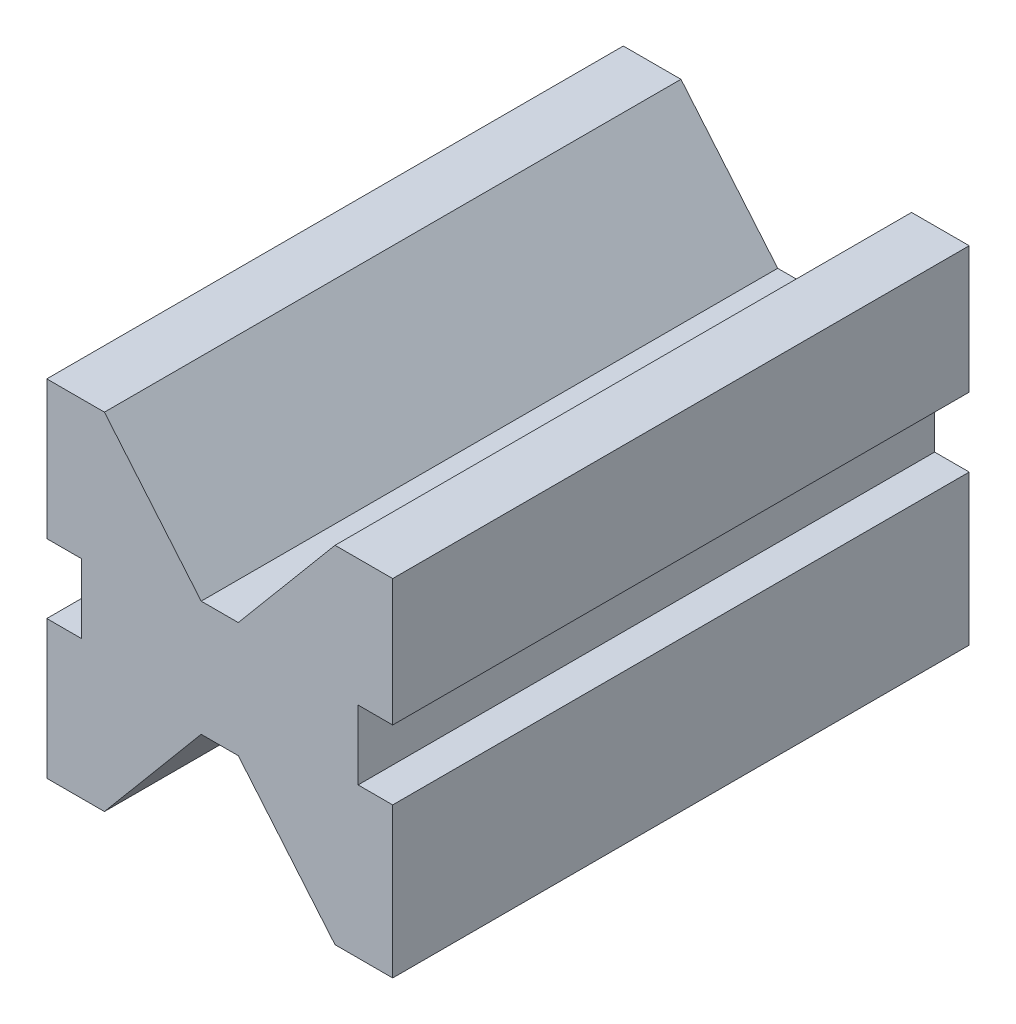
SolidWorks part; units mm, degrees
ref_plane "Ön Düzlem" through (0, 0, 0) normal (0, 0, 1) x (1, 0, 0)
ref_plane "Üst Düzlem" through (0, 0, 0) normal (0, 1, 0) x (1, 0, 0)
ref_plane "Sağ Düzlem" through (0, 0, 0) normal (1, 0, 0) x (0, 0, -1)
sketch "Çizim1" plane through (0, 0, 0) normal (0, 0, 1) x (1, 0, 0)
  line L0 (-50, 60) -> (-33.218, 40)
  line L1 (0, 0) -> (-10, 0)
  line L2 (0, 0) -> (0, 26.0026)
  line L3 (0, 60) -> (-10, 60)
  line L4 (-60, 0) -> (-60, 24)
  line L5 (-60, 36) -> (-54, 36)
  line L7 (-60, 24) -> (-54, 24)
  line L8 (-54, 36) -> (-54, 24)
  line L9 (0, 26.0026) -> (-6, 26.0026)
  line L11 (0, 38.0026) -> (-6, 38.0026)
  line L12 (-6, 26.0026) -> (-6, 38.0026)
  line L13 (-33.218, 40) -> (-26.782, 40)
  line L14 (-26.782, 40) -> (-10, 60)
  line L15 (-50, 0) -> (-33.218, 20)
  line L16 (-33.218, 20) -> (-26.782, 20)
  line L17 (-26.782, 20) -> (-10, 0)
  line L18 (-50, 60) -> (-60, 60)
  line L19 (-60, 36) -> (-60, 60)
  line L20 (-50, 0) -> (-60, 0)
  line L21 (0, 38.0026) -> (0, 60)
  dimension "D1" = 130
  dimension "D2" = 130
  dimension "D3" = 130
  dimension "D4" = 130
  dimension "D5" = 10
  dimension "D6" = 10
  dimension "D7" = 10
  dimension "D8" = 10
  dimension "D9" = 60
  dimension "D10" = 20
  dimension "D11" = 24
  dimension "D12" = 36
  dimension "D13" = 60
  dimension "D14" = 12
  dimension "D15" = 6
  dimension "D16" = 6
  dimension "D17" = 20
extrude "Yükseklik-Ekstrüzyon1" add sketch "Çizim1" along normal blind 100
